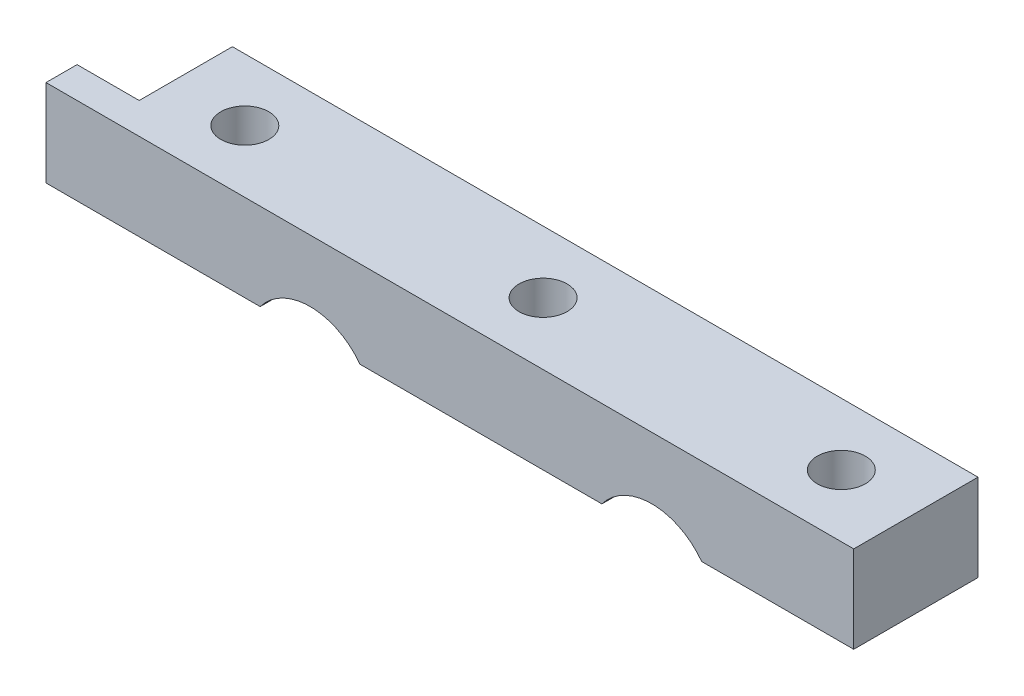
SolidWorks part; units mm, degrees
material "6061-T6 (SS)"
ref_plane "Front Plane" through (0, 0, 0) normal (0, 0, 1) x (1, 0, 0)
ref_plane "Top Plane" through (0, 0, 0) normal (0, 1, 0) x (1, 0, 0)
ref_plane "Right Plane" through (0, 0, 0) normal (1, 0, 0) x (0, 0, -1)
sketch "Sketch1" plane through (0, 0, 0) normal (0, 0, 1) x (1, 0, 0)
  line L0 (-38.1, 17.145) -> (-38.1, 24.7142) construction
  line L3 (-38.1, 17.145) -> (-22.5615, 17.145) construction
  line L5 (38.1, 33.6042) -> (38.1, 24.7142)
  line L6 (22.5615, 24.7142) -> (38.1, 24.7142)
  line L7 (-38.1, 24.7142) -> (-22.5615, 24.7142)
  line L8 (-38.1, 24.7142) -> (-38.1, 33.6042)
  line L9 (-38.1, 33.6042) -> (38.1, 33.6042)
  line L10 (-38.1, 20.9296) -> (38.1, 20.9296) construction
  line L11 (-12.3635, 24.7142) -> (12.3635, 24.7142)
  line L12 (-12.3635, 17.145) -> (12.3635, 17.145) construction
  line L13 (22.5615, 17.145) -> (38.1, 17.145) construction
  arc A0 (-12.3635, 24.7142) -> (-22.5615, 24.7142) centre (-17.4625, 20.9296) ccw
  arc A1 (22.5615, 17.145) -> (12.3635, 17.145) centre (17.4625, 20.9296) cw construction
  arc A2 (-22.5615, 17.145) -> (-12.3635, 17.145) centre (-17.4625, 20.9296) ccw construction
  arc A3 (12.3635, 24.7142) -> (22.5615, 24.7142) centre (17.4625, 20.9296) cw
  point P5 (-22.5615, 24.7142)
  dimension "D5" = 76.2
  dimension "D6" = 34.925
  dimension "D7" = 6.35
  dimension "D8" = 6.35
  dimension "D9" = 38.1
  dimension "D2" = 17.4625
  dimension "D1" = 17.145
  dimension "D3" = 8.89
  dimension "D4" = 7.5692
extrude "Boss-Extrude1" add sketch "Sketch1" along normal blind 12.7
sketch "Sketch2" plane through (-38.1, 0, 0) normal (-1, 0, 0) x (0, 0, 1)
  line L0 (12.7, 24.7142) -> (0, 24.7142) construction
  line L1 (12.7, 33.6042) -> (9.525, 33.6042)
  line L2 (12.7, 33.6042) -> (12.7, 24.7142)
  line L3 (12.7, 24.7142) -> (9.525, 24.7142)
  line L4 (9.525, 33.6042) -> (9.525, 24.7142)
  line L5 (0, 33.6042) -> (0, 24.7142) construction
  dimension "D1" = 9.525
extrude "Boss-Extrude2" add sketch "Sketch2" along normal blind 6.35
sketch "Sketch3" plane through (0, 33.6042, 0) normal (0, 1, 0) x (1, 0, 0)
  line L0 (38.1, -6.35) -> (-38.1, -6.35) construction
  line L1 (38.1, -12.7) -> (38.1, 0) construction
  line L2 (-38.1, -9.525) -> (-38.1, 0) construction
  point P6 (0, -6.35)
  point P7 (-30.48, -6.35)
  point P8 (30.48, -6.35)
  dimension "D1" = 7.62
  dimension "D2" = 7.62
hole_wizard "#10 (0.1935) Diameter Hole1" positions "3DSketch1" profile "Sketch4" hole size "#10" standard "ANSI Inch" end condition through all
sketch3d "3DSketch1"
  point P0 (-30.48, 33.6042, 6.35)
  point P3 (0, 33.6042, 6.35)
  point P6 (30.48, 33.6042, 6.35)
sketch "Sketch4" plane through (-30.48, 33.6042, 6.35) normal (1, 0, 0) x (0, 0, 1)
  line L0 (0, 0) -> (0, 8.89)
  line L1 (0, 8.89) -> (2.4574, 8.89)
  line L2 (2.4574, 8.89) -> (2.4574, 0)
  line L5 (2.4574, 0) -> (0, 0)
  line L11 (0, -6.35) -> (0, 107.95) construction
  dimension "Thru Hole Dia." = 4.9149
  dimension "Thru Hole Depth" = 8.89
